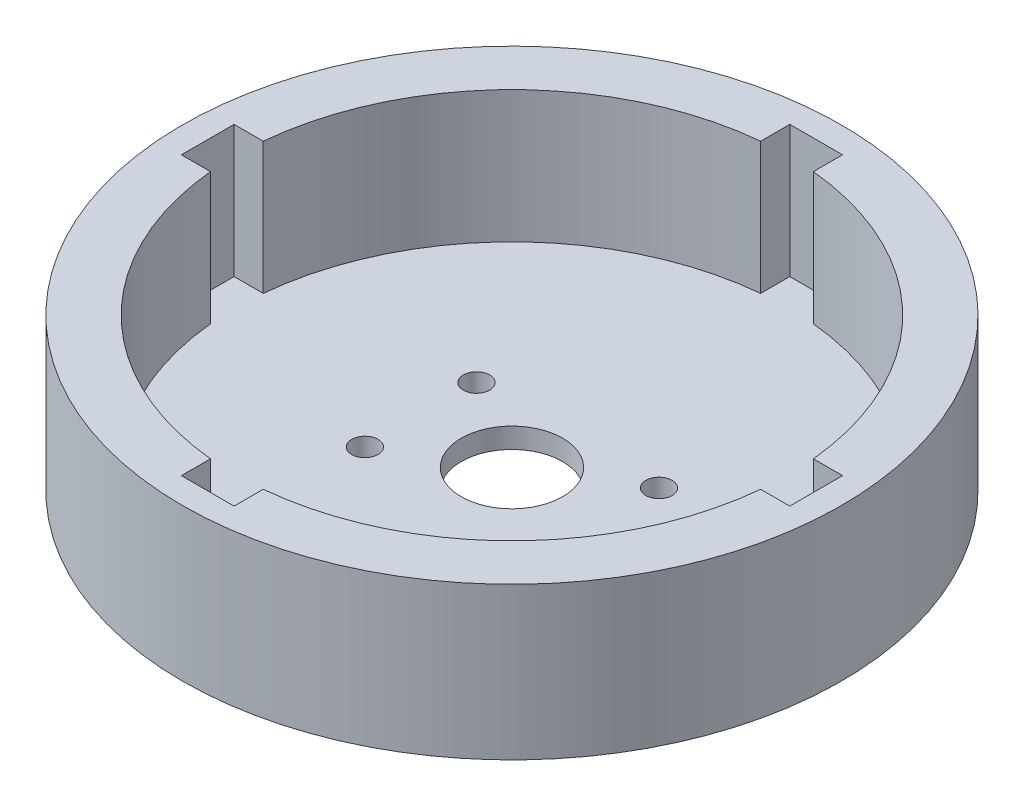
SolidWorks part; units mm, degrees
ref_plane "Front Plane" through (0, 0, 0) normal (0, 0, 1) x (1, 0, 0)
ref_plane "Top Plane" through (0, 0, 0) normal (0, 1, 0) x (1, 0, 0)
ref_plane "Right Plane" through (0, 0, 0) normal (1, 0, 0) x (0, 0, -1)
sketch "Sketch1" plane through (0, 0, 0) normal (0, 1, 0) x (1, 0, 0)
  circle A0 centre (0, 0) radius 32.5
  dimension "D1" = 65
extrude "Boss-Extrude1" add sketch "Sketch1" along normal blind 2
sketch "Sketch2" plane through (0, 2, 0) normal (0, 1, 0) x (1, 0, 0)
  line L0 (0, -55) -> (0, 55) construction
  line L1 (2.6, -30) -> (-2.6, -30)
  line L2 (2.6, -30) -> (2.6, -26.0456)
  line L3 (2.6, -26.0456) -> (-2.6, -26.0456)
  line L4 (-2.6, -30) -> (-2.6, -26.0456)
  line L5 (2.6, -30) -> (-2.6, -26.0456) construction
  line L6 (2.6, -26.0456) -> (-2.6, -30) construction
  line L7 (-30, -2.6) -> (-30, 2.6)
  line L8 (-30, -2.6) -> (-26.0456, -2.6)
  line L9 (-30, 2.6) -> (-26.0456, 2.6)
  line L10 (-26.0456, -2.6) -> (-26.0456, 2.6)
  line L11 (-2.6, 30) -> (2.6, 30)
  line L12 (-2.6, 30) -> (-2.6, 26.0456)
  line L13 (2.6, 30) -> (2.6, 26.0456)
  line L14 (-2.6, 26.0456) -> (2.6, 26.0456)
  line L15 (30, 2.6) -> (30, -2.6)
  line L16 (30, 2.6) -> (26.0456, 2.6)
  line L17 (30, -2.6) -> (26.0456, -2.6)
  line L18 (26.0456, 2.6) -> (26.0456, -2.6)
  circle A0 centre (0, 0) radius 27.1
  circle A1 centre (0, 0) radius 27.25
  circle A2 centre (0, 0) radius 32.5
  point P4 (0, -28.0228)
  circle M7 centre (0, 0) radius 32.5
  dimension "D1" = 54.5
  dimension "D2" = 54.2
  dimension "D3" = 30
  dimension "D4" = 5.2
  dimension "D5" = 4
extrude "Boss-Extrude2" add sketch "Sketch2" along normal blind 13 contours A0 L2 L1 L4 L8 L7 L9 L12 L11 L13 L16 L15 L17 M7
sketch "Sketch3" plane through (0, 0, 0) normal (0, -1, 0) x (1, 0, 0)
  circle A5 centre (0, 0) radius 5
  dimension "D1" = 10
extrude "Cut-Extrude2" cut sketch "Sketch3" against normal up to next contours A5
sketch "Sketch5" plane through (0, 0, 0) normal (0, -1, 0) x (1, 0, 0)
  line L1 (-9, -5.5) -> (9, -5.5) construction
  line L2 (-9, -5.5) -> (-9, 5.5) construction
  line L3 (-9, 5.5) -> (9, 5.5) construction
  line L4 (9, -5.5) -> (9, 5.5) construction
  line L5 (-9, -5.5) -> (9, 5.5) construction
  line L6 (-9, 5.5) -> (9, -5.5) construction
  circle A0 centre (9, 5.5) radius 1.3
  circle A1 centre (9, -5.5) radius 1.3
  circle A2 centre (-9, -5.5) radius 1.3
  circle A3 centre (-9, 5.5) radius 1.3
  point P0 (0, 0)
  dimension "D1" = 2.6
  dimension "D2" = 18
  dimension "D3" = 11
extrude "Cut-Extrude3" cut sketch "Sketch5" against normal up to next
